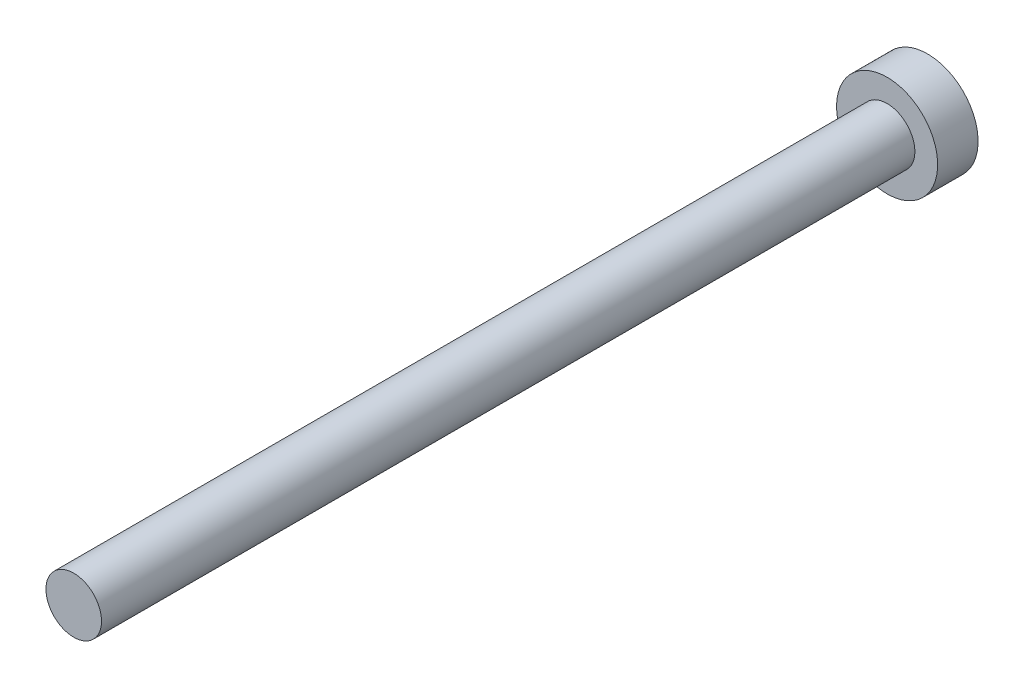
SolidWorks part; units mm, degrees
ref_plane "Front Plane" through (0, 0, 0) normal (0, 0, 1) x (1, 0, 0)
ref_plane "Top Plane" through (0, 0, 0) normal (0, 1, 0) x (1, 0, 0)
ref_plane "Right Plane" through (0, 0, 0) normal (1, 0, 0) x (0, 0, -1)
sketch "Sketch1" plane through (0, 0, 0) normal (0, 0, 1) x (1, 0, 0)
  circle A0 centre (0, 0) radius 1.5
  dimension "D1" = 3
extrude "Boss-Extrude1" add sketch "Sketch1" along normal blind 42
sketch "Sketch2" plane through (0, 0, 0) normal (0, 0, -1) x (-1, 0, 0)
  circle A0 centre (0, 0) radius 2.75
  dimension "D1" = 5.5
extrude "Boss-Extrude2" add sketch "Sketch2" against normal blind 2.2
scale "Escala1" scale about origin uniform scaling yes scale factor 1.5
scale "Escala2" scale about origin uniform scaling yes scale factor 1.5
sketch "Croquis1" plane through (0, 0, 94.5) normal (0, 0, 1) x (1, 0, 0)
  circle A2 centre (0, 0) radius 3.375 construction
  circle A3 centre (0, 0) radius 3.375 construction
  circle A4 centre (0, 0) radius 3.4
  dimension "D1" = 6.8
extrude "Saliente-Extruir1" add sketch "Croquis1" along normal blind 10 and the other way up to next
